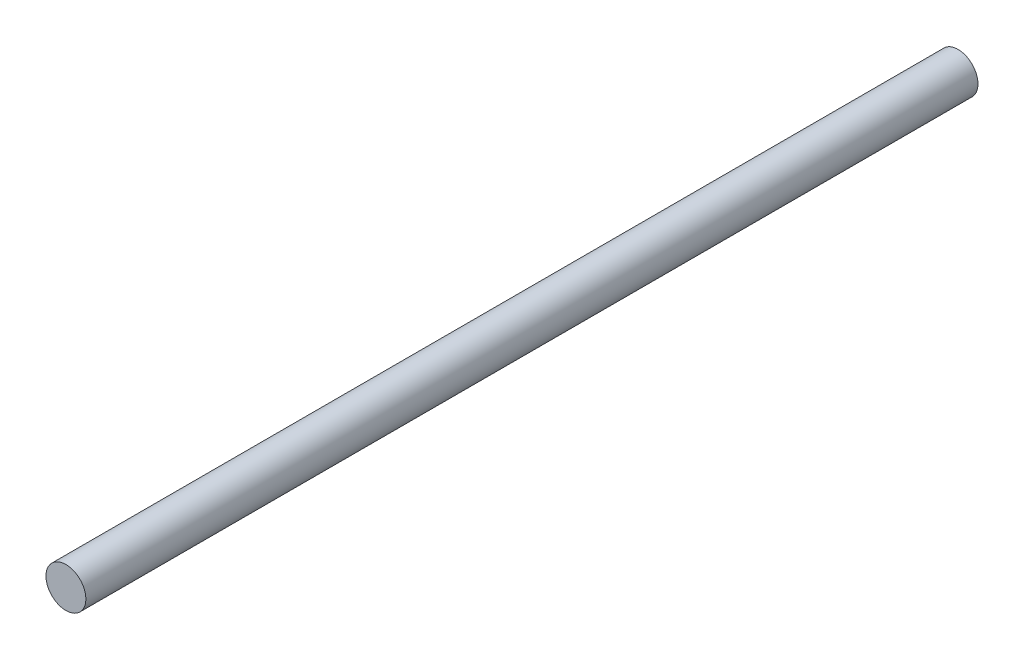
SolidWorks part; units mm, degrees
material "AISI 316 Annealed Stainless Steel Bar (SS)"
ref_plane "Front Plane" through (0, 0, 0) normal (0, 0, 1) x (1, 0, 0)
ref_plane "Top Plane" through (0, 0, 0) normal (0, 1, 0) x (1, 0, 0)
ref_plane "Right Plane" through (0, 0, 0) normal (1, 0, 0) x (0, 0, -1)
sketch "Sketch1" plane through (0, 0, 0) normal (0, 0, 1) x (1, 0, 0)
  circle A0 centre (0, 0) radius 3.9751
  dimension "Diameter" = 7.9502
extrude "Boss-Extrude1" add sketch "Sketch1" against normal blind 177.8
sketch "Sketch2" plane through (0, 0, 0) normal (0, 0, 1) x (1, 0, 0)
  line L0 (0, 0) -> (-3.9751, 0)
  circle A0 centre (0, 0) radius 3.9751 construction
  point P0 (0, 0)
